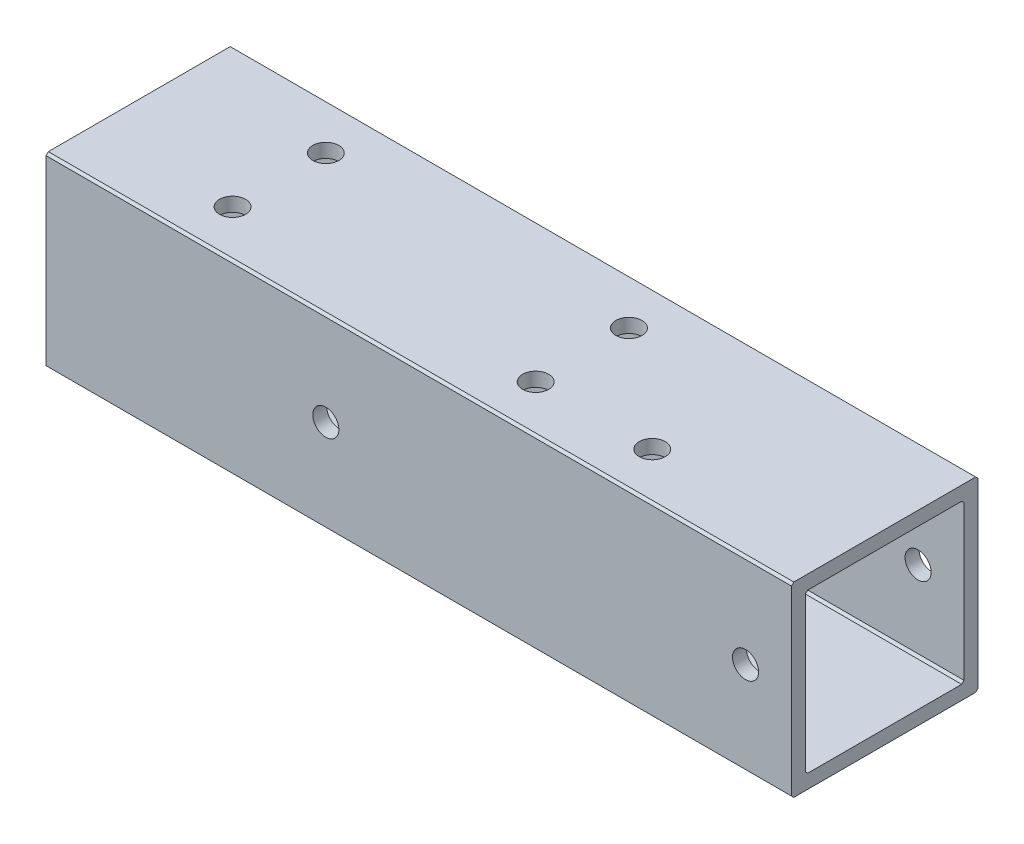
SolidWorks part; units mm, degrees
ref_plane "Front Plane" through (0, 0, 0) normal (0, 0, 1) x (1, 0, 0)
ref_plane "Top Plane" through (0, 0, 0) normal (0, 1, 0) x (1, 0, 0)
ref_plane "Right Plane" through (0, 0, 0) normal (1, 0, 0) x (0, 0, -1)
ref_plane "Plane1" through (0, -102, 0) normal (0, 1, 0) x (1, 0, 0)
sketch "Sketch1" plane through (0, -102, 0) normal (0, 1, 0) x (1, 0, 0)
  line L0 (-90.15, -140) -> (-90.15, -100)
  line L1 (-90.15, -100) -> (-250, -100)
  line L2 (-250, -100) -> (-250, -140)
  line L3 (-250, -140) -> (-90.15, -140)
extrude "Boss-Extrude1" add sketch "Sketch1" against normal blind 40
sketch "Sketch2" plane through (-250, 0, 0) normal (-1, 0, 0) x (0, 0, 1)
  line L0 (103, -139) -> (137, -139)
  line L1 (137, -139) -> (137, -105)
  line L2 (137, -105) -> (103, -105)
  line L3 (103, -105) -> (103, -139)
extrude "Cut-Extrude1" cut sketch "Sketch2" against normal through all
hole_wizard "Ø5.6 (5.6) Diameter Hole1" positions "Sketch4" profile "Sketch3" hole size "Ø5.6" standard "ANSI Metric"
sketch "Sketch4" plane through (0, -139, 0) normal (0, 1, 0) x (1, 0, 0)
  point P0 (-130, -130)
  point P1 (-155, -130)
  point P2 (-155, -110)
  point P3 (-220, -130)
  point P4 (-220, -110)
sketch "Sketch3" plane through (-130, -139, 130) normal (1, 0, 0) x (0, 0, 1)
  line L0 (0, 0) -> (0, 3)
  line L1 (0, 3) -> (2.8, 3)
  line L2 (2.8, 3) -> (2.8, 0)
  line L5 (2.8, 0) -> (0, 0)
  line L11 (0, -6.35) -> (0, 107.95) construction
  dimension "Thru Hole Dia." = 5.6
  dimension "Thru Hole Depth" = 3
hole_wizard "Ø5.6 (5.6) Diameter Hole2" positions "Sketch6" profile "Sketch5" hole size "Ø5.6" standard "ANSI Metric"
sketch "Sketch6" plane through (0, 0, 100) normal (0, 0, -1) x (-1, 0, 0)
  point P0 (100, -122)
  point P1 (190, -122)
sketch "Sketch5" plane through (-100, -122, 100) normal (1, 0, 0) x (0, 1, 0)
  line L0 (0, 0) -> (0, 3)
  line L1 (0, 3) -> (2.8, 3)
  line L2 (2.8, 3) -> (2.8, 0)
  line L5 (2.8, 0) -> (0, 0)
  line L11 (0, -6.35) -> (0, 107.95) construction
  dimension "Thru Hole Dia." = 5.6
  dimension "Thru Hole Depth" = 3
hole_wizard "Ø5.6 (5.6) Diameter Hole3" positions "Sketch8" profile "Sketch7" hole size "Ø5.6" standard "ANSI Metric"
sketch "Sketch8" plane through (0, 0, 137) normal (0, 0, -1) x (-1, 0, 0)
  point P0 (100, -122)
  point P1 (190, -122)
sketch "Sketch7" plane through (-100, -122, 137) normal (1, 0, 0) x (0, 1, 0)
  line L0 (0, 0) -> (0, 3)
  line L1 (0, 3) -> (2.8, 3)
  line L2 (2.8, 3) -> (2.8, 0)
  line L5 (2.8, 0) -> (0, 0)
  line L11 (0, -6.35) -> (0, 107.95) construction
  dimension "Thru Hole Dia." = 5.6
  dimension "Thru Hole Depth" = 3
hole_wizard "Ø5.6 (5.6) Diameter Hole4" positions "Sketch10" profile "Sketch9" hole size "Ø5.6" standard "ANSI Metric"
sketch "Sketch10" plane through (0, -102, 0) normal (0, 1, 0) x (1, 0, 0)
  point P0 (-130, -130)
  point P1 (-155, -130)
  point P2 (-155, -110)
  point P3 (-220, -130)
  point P4 (-220, -110)
sketch "Sketch9" plane through (-130, -102, 130) normal (1, 0, 0) x (0, 0, 1)
  line L0 (0, 0) -> (0, 40)
  line L1 (0, 40) -> (2.8, 40)
  line L2 (2.8, 40) -> (2.8, 0)
  line L5 (2.8, 0) -> (0, 0)
  line L11 (0, -6.35) -> (0, 107.95) construction
  dimension "Thru Hole Dia." = 5.6
  dimension "Thru Hole Depth" = 40
chamfer "Chamfer1" distance 0.5 angle 45 8 edges at (-170.075, -142, 100) (-170.075, -102, 100) (-170.075, -102, 140) (-170.075, -105, 137) (-170.075, -142, 140) (-170.075, -139, 103) (-170.075, -139, 137) (-170.075, -105, 103)
